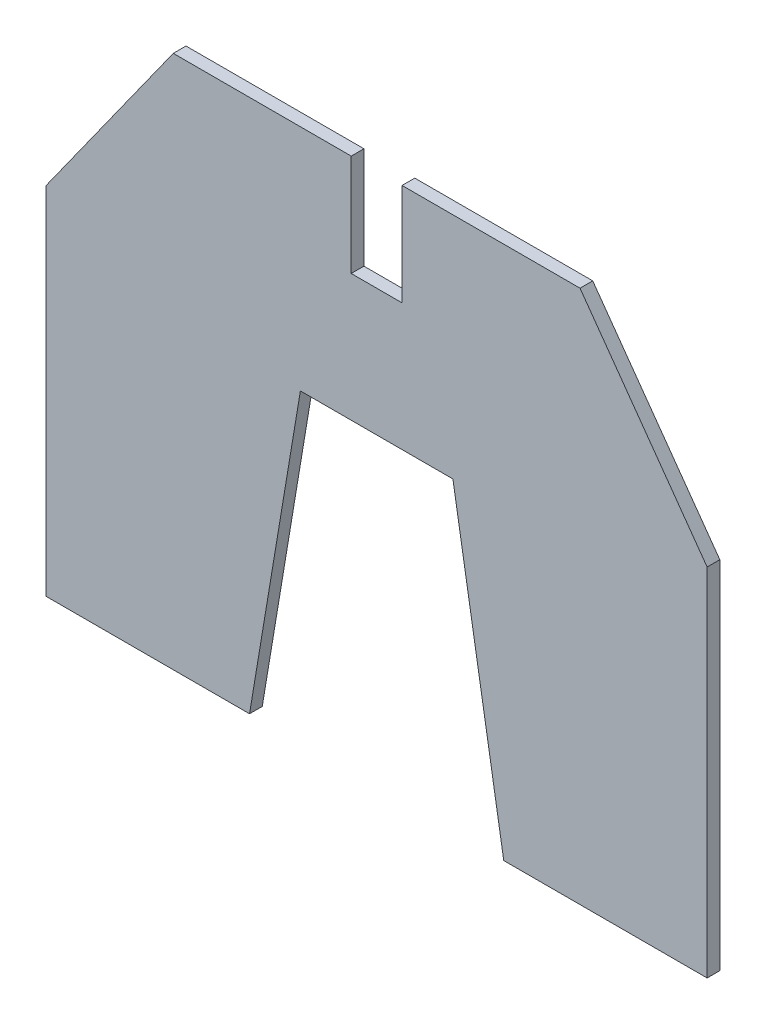
SolidWorks part; units mm, degrees
ref_plane "Ebene vorne" through (0, 0, 0) normal (0, 0, 1) x (1, 0, 0)
ref_plane "Ebene oben" through (0, 0, 0) normal (0, 1, 0) x (1, 0, 0)
ref_plane "Ebene rechts" through (0, 0, 0) normal (1, 0, 0) x (0, 0, -1)
sketch "Skizze1" plane through (0, 0, 0) normal (0, 0, 1) x (1, 0, 0)
  line L0 (0, 0) -> (0, 110.2869) construction
  line L1 (-15, 60) -> (15, 60)
  line L2 (15, 60) -> (25, 0)
  line L3 (25, 0) -> (65, 0)
  line L4 (65, 0) -> (65, 70)
  line L5 (65, 70) -> (40, 105)
  line L6 (40, 105) -> (5, 105)
  line L7 (5, 105) -> (5, 85)
  line L8 (5, 85) -> (-5, 85)
  line L9 (-5, 105) -> (-5, 85)
  line L10 (-40, 105) -> (-5, 105)
  line L11 (-65, 70) -> (-40, 105)
  line L12 (-65, 0) -> (-65, 70)
  line L13 (-25, 0) -> (-65, 0)
  line L14 (-15, 60) -> (-25, 0)
  point P13 (0, 85)
  point P19 (0, 60)
  dimension "D1" = 30
  dimension "D2" = 50
  dimension "D3" = 60
  dimension "D4" = 105
  dimension "D5" = 70
  dimension "D6" = 10
  dimension "D7" = 80
  dimension "D8" = 130
  dimension "D9" = 20
extrude "Aufsatz-Linear austragen1" add sketch "Skizze1" along normal blind 2.5
